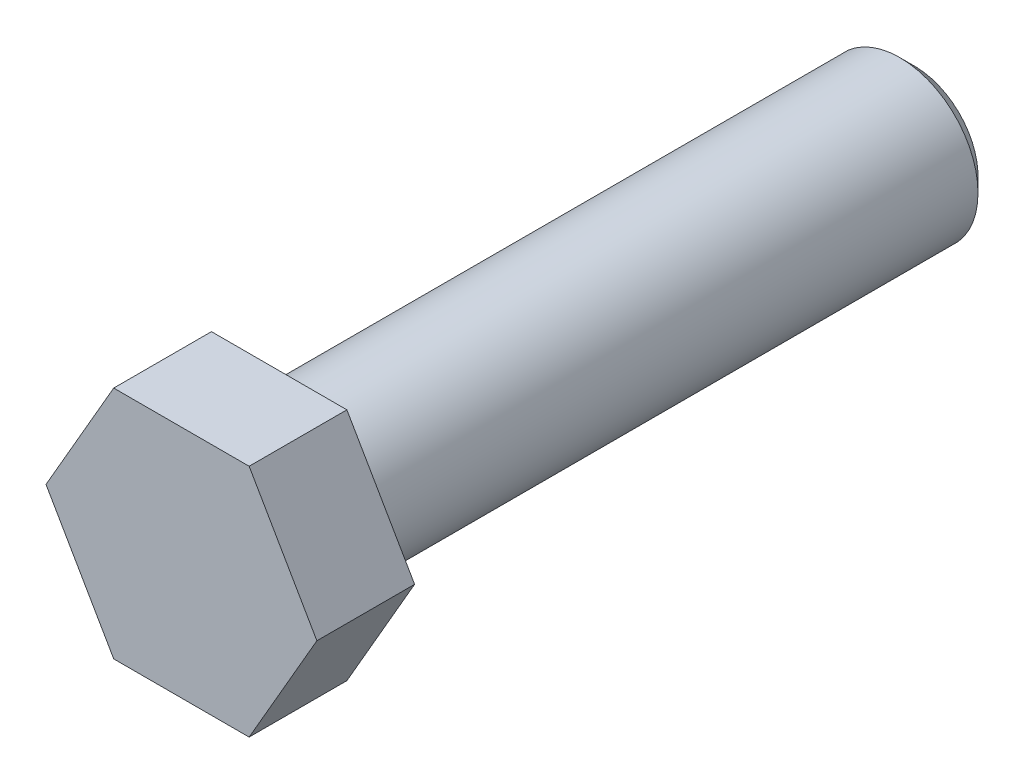
SolidWorks part; units mm, degrees
ref_plane "Plane1" through (0, 0, 0) normal (0, 0, 1) x (1, 0, 0)
ref_plane "MSC_PF1" through (0, 0, 0) normal (0, 1, 0) x (1, 0, 0)
ref_plane "Plane3" through (0, 0, 0) normal (1, 0, 0) x (0, 0, -1)
sketch "Sketch1" plane through (0, 0, 0) normal (0, 0, 1) x (1, 0, 0)
  line L0 (0, 0) -> (1, 0) construction
  line L1 (-6.9282, 12) -> (6.9282, 12)
  line L2 (-6.9282, -12) -> (6.9282, -12)
  line L3 (6.9282, 12) -> (13.8564, 0)
  line L4 (13.8564, 0) -> (6.9282, -12)
  line L5 (-6.9282, 12) -> (-13.8564, 0)
  line L6 (-13.8564, 0) -> (-6.9282, -12)
  circle A0 centre (0, 0) radius 12 construction
  dimension "P" = 1
  dimension "s" = 24
extrude "Base-Extrude" add sketch "Sketch1" along normal blind 10
sketch "Sketch3" plane through (0, 0, 0) normal (0, 0, -1) x (-1, 0, 0)
  circle A0 centre (0, 0) radius 8
  dimension "_d" = 16
extrude "Boss-Extrude1" add sketch "Sketch3" along normal blind 65
cosmetic thread "Условное изображение резьбы2" parameters "D2"=15
chamfer "Chamfer1" distance 1.5 angle 45 1 edges at (-8, 0, -65)
